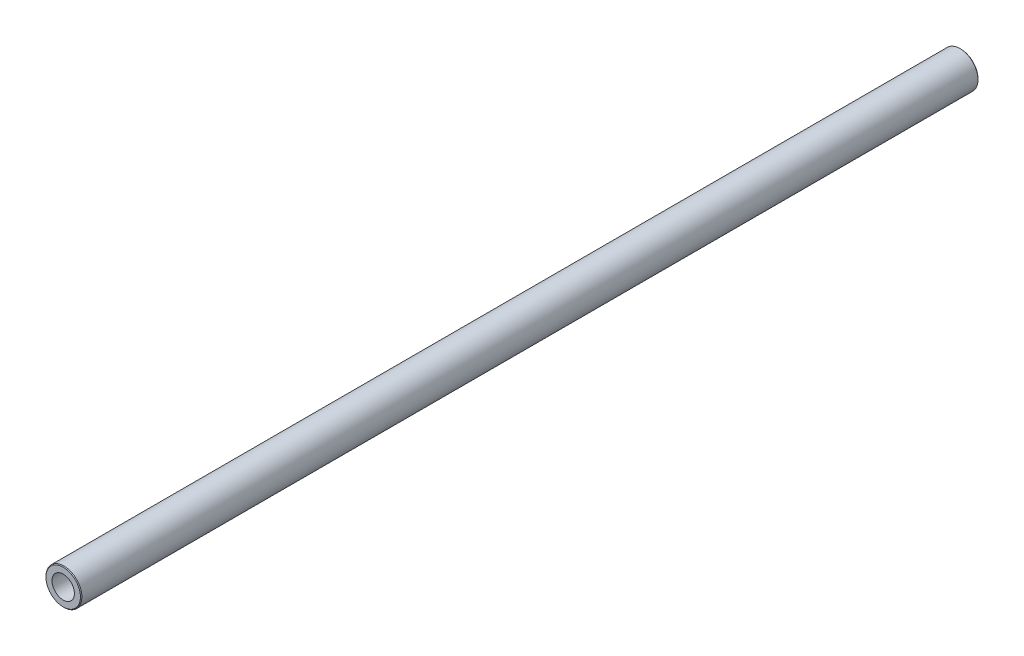
SolidWorks part; units mm, degrees
ref_plane "Front Plane" through (0, 0, 0) normal (0, 0, 1) x (1, 0, 0)
ref_plane "Top Plane" through (0, 0, 0) normal (0, 1, 0) x (1, 0, 0)
ref_plane "Right Plane" through (0, 0, 0) normal (1, 0, 0) x (0, 0, -1)
sketch "Sketch1" plane through (0, 0, 0) normal (0, 0, 1) x (1, 0, 0)
  circle A0 centre (0, 0) radius 4 construction
  dimension "Diameter" = 8
sketch "Sketch2" plane through (0, 0, 0) normal (1, 0, 0) x (0, 0, -1)
  line L0 (100, 0) -> (-100, 0) construction
  point P0 (-80, 0)
  point P3 (0, 0)
  point P4 (80, 0)
  point P6 (-70, 0)
  point P7 (70, 0)
  dimension "Length" = 200
  dimension "D1" = 20
  dimension "D2" = 20
  dimension "D3" = 30
  dimension "D4" = 30
sketch "Sketch3" plane through (0, 0, 0) normal (0, 0, 1) x (1, 0, 0)
  circle A0 centre (0, 0) radius 4 construction
  circle A1 centre (0, 0) radius 4
extrude "Boss-Extrude1" add sketch "Sketch3" along normal up to vertex (100 mm away) and the other way up to vertex (100 mm away) up to point (0, 0, 100) other way up to point (0, 0, -100)
chamfer "Chamfer1" distance 0.16 angle 45 2 edges at (4, 0, 100) (4, 0, -100)
hole_wizard "M6x1.0 Tapped Hole1" positions "3DSketch1" profile "Sketch4" tap size "M6x1.0" standard "ANSI Metric"
sketch3d "3DSketch1"
  line L0 (0, 0, 99.84) -> (0, 0, 100) construction
  line L1 (0, 0, -99.84) -> (0, 0, -100) construction
  point P0 (0, 0, 100)
  point P4 (0, 0, -100)
sketch "Sketch4" plane through (0, 0, 100) normal (1, 0, 0) x (0, -1, 0)
  line L0 (0, 0) -> (0, 26.5022)
  line L1 (0, 26.5022) -> (2.5, 25)
  line L2 (2.5, 25) -> (2.5, 0)
  line L5 (2.5, 0) -> (0, 0)
  line L10 (0, 26.5022) -> (-2.5, 25) construction
  line L11 (0, -6.35) -> (0, 107.95) construction
  dimension "Tap Drill Dia." = 5
  dimension "Tap Drill Depth" = 25
  dimension "Drill Angle" = 118
cosmetic thread "Hole Thread1" parameters "D1"=12, "D2"=6
cosmetic thread "Hole Thread2" parameters "D1"=12, "D2"=6
equation "\"D1@Chamfer1\"=\"Diameter@Sketch1\"*.02"
equation "\"D1@Sketch2\"=\"D2@Sketch2\""
equation "\"D2@Sketch2\"=\"Length@Sketch2\"*.1"
equation "\"D3@Sketch2\"=\"Length@Sketch2\"*.15"
equation "\"D4@Sketch2\"=\"D3@Sketch2\""
